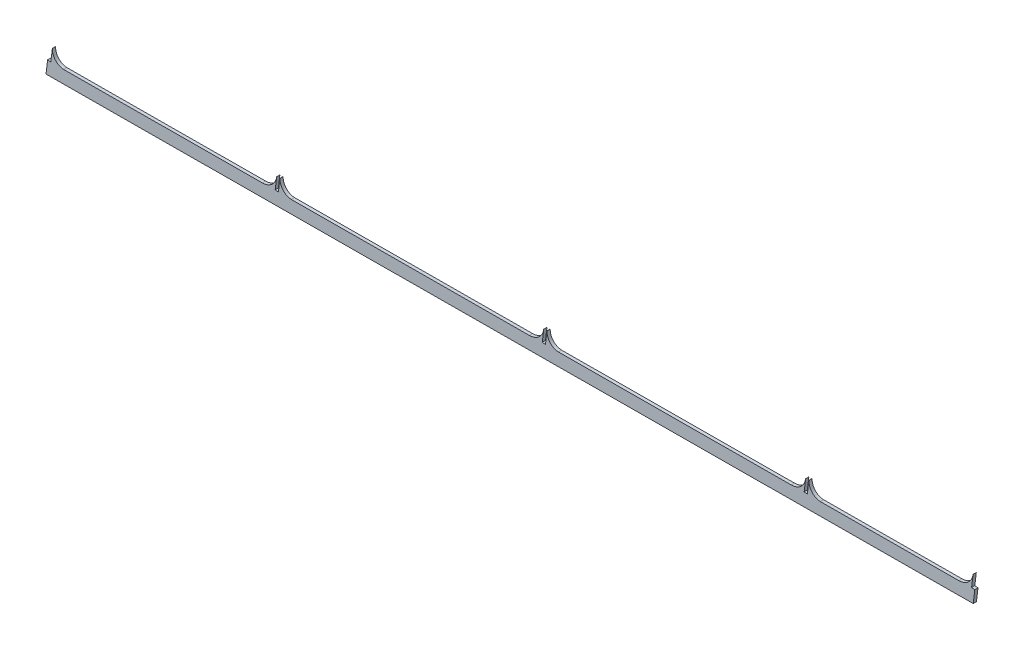
SolidWorks part; units mm, degrees
ref_plane "前视基准面" through (0, 0, 0) normal (0, 0, 1) x (1, 0, 0)
ref_plane "上视基准面" through (0, 0, 0) normal (0, 1, 0) x (1, 0, 0)
ref_plane "右视基准面" through (0, 0, 0) normal (1, 0, 0) x (0, 0, -1)
sketch "Model" plane through (0, 0, 0) normal (0, 0, 1) x (1, 0, 0)
  line L0 (4.1376, 9.8478) -> (580.8731, 12.9956)
  line L1 (7.1252, 17.7991) -> (5.1438, 18.0424)
  line L2 (148.6837, 18.5718) -> (146.7023, 18.815)
  line L3 (314.8061, 19.4785) -> (312.8247, 19.7217)
  line L4 (477.6903, 20.3675) -> (475.709, 20.6108)
  line L5 (581.8481, 20.936) -> (579.8667, 21.1792)
  line L6 (8.1001, 25.7395) -> (7.1252, 17.7991)
  line L7 (5.1438, 18.0424) -> (4.1376, 9.8478)
  line L8 (147.646, 26.5011) -> (146.7023, 18.815)
  line L9 (148.6837, 18.5718) -> (149.6586, 26.5121)
  line L10 (313.7684, 27.4078) -> (312.8247, 19.7217)
  line L11 (314.8061, 19.4785) -> (315.781, 27.4188)
  line L12 (476.6527, 28.2969) -> (475.709, 20.6108)
  line L13 (477.6903, 20.3675) -> (478.6653, 28.3078)
  line L14 (580.8104, 28.8653) -> (579.8667, 21.1792)
  line L15 (581.8481, 20.936) -> (580.8731, 12.9956)
  line L16 (15.125, 17.8428) -> (138.6712, 18.5171)
  line L17 (156.6836, 18.6154) -> (304.7936, 19.4238)
  line L18 (322.8059, 19.5221) -> (467.6779, 20.3128)
  line L19 (485.6902, 20.4111) -> (571.9121, 20.8814)
  arc A0 (8.1001, 25.7395) -> (15.125, 17.8428) centre (15.5451, 25.2895) ccw
  arc A1 (149.6586, 26.5121) -> (156.6836, 18.6154) centre (157.1036, 26.0621) ccw
  arc A2 (315.781, 27.4188) -> (322.8059, 19.5221) centre (323.2259, 26.9688) ccw
  arc A3 (478.6653, 28.3078) -> (485.6902, 20.4111) centre (486.1102, 27.8578) ccw
  arc A4 (138.6712, 18.5171) -> (147.646, 26.5011) centre (138.6986, 27.5226) ccw
  arc A5 (304.7936, 19.4238) -> (313.7684, 27.4078) centre (304.821, 28.4293) ccw
  arc A6 (467.6779, 20.3128) -> (476.6527, 28.2969) centre (467.7053, 29.3184) ccw
  arc A7 (571.9121, 20.8814) -> (580.8104, 28.8653) centre (571.863, 29.8868) ccw
  point P37 (571.9043, 20.8814)
extrude "凸台-拉伸1" add sketch "Model" along normal blind 2 contours A7 L19 A3 L13 L4 L12 A6 L18 A2 L11 L3 L10 A5 L17 A1 L9 L2 L8 A4 L16 A0 L6 L1 L7 L0 L15 L5 L14
